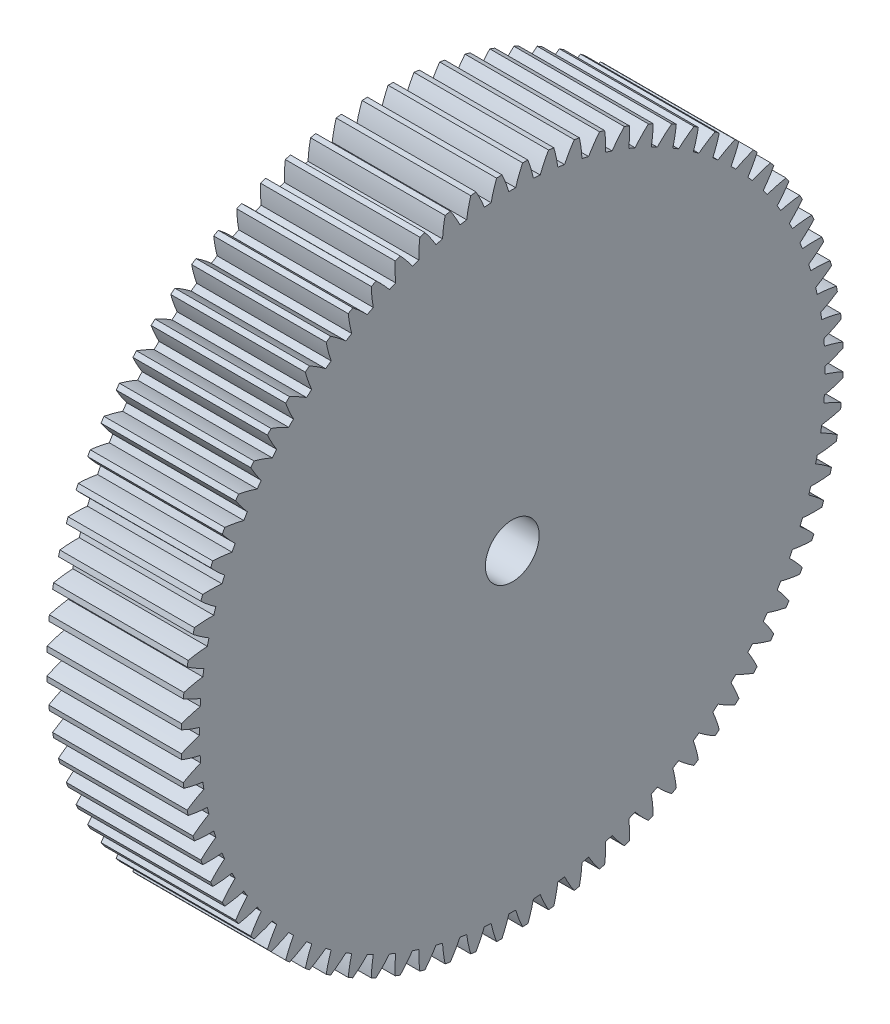
SolidWorks part; units mm, degrees
ref_plane "Plane1" through (0, 0, 0) normal (0, 0, 1) x (1, 0, 0)
ref_plane "Plane2" through (0, 0, 0) normal (0, 1, 0) x (1, 0, 0)
ref_plane "Plane3" through (0, 0, 0) normal (1, 0, 0) x (0, 0, -1)
other "Configuration Table"
sketch "HoldingSke" plane through (0, 0, 0) normal (0, 1, 0) x (1, 0, 0)
  line L0 (0, 0) -> (0.2894, -1.6413)
  line L1 (-15, 0) -> (100, 0) construction
  line L2 (0, 0) -> (-2.1039, 2.3779)
  line L3 (0, 0) -> (-11.863, 4.5341)
  line L4 (0, 0) -> (1.4996, 8.5048)
  line L5 (0, 0) -> (-46.8476, -17.4728)
  line L6 (0, 0) -> (-8.2896, -5.593)
  line L7 (-2.1039, 2.3779) -> (8.6586, 51.2059)
  line L8 (-76.2, 54.61) -> (-75.5, 54.61)
  line L9 (-71.009, 38.7566) -> (-53.1078, 45.2721)
  line L10 (-76.2, 71.12) -> (104.1128, 71.12)
  line L11 (0, 0) -> (-10, 0)
  line L12 (-76.2, 101.6) -> (-76.177, 101.6)
  line L13 (24.9733, 27.94) -> (52.9518, 28.4284)
  line L14 (24.9733, 27.94) -> (24.9743, 27.94)
  line L15 (24.9733, 27.94) -> (100.4006, 29.5858)
  line L16 (-63.627, -0.6) -> (-12.827, -0.6)
  circle A0 centre (0, 0) radius 2
  circle A1 centre (0, 0) radius 23.249
  circle A2 centre (0, 0) radius 37.5
  circle A3 centre (0, 0) radius 2
  dimension "MHD" = 46.498
  dimension "Hub_dia" = 75
  dimension "Bore" = 4
  dimension "MBD" = 4
  dimension "Num_teeth" = 80
  dimension "Pitch" = 1.6667
  dimension "Overall_len" = 50
  dimension "Show_teeth" = 80
  dimension "Thickness" = 10
  dimension "OAL" = 50.0001
  dimension "T_dim" = 0.7
  dimension "Ap" = 20
  dimension "H" = 19.05
  dimension "Pitch_radius" = 180.3128
  dimension "Width" = 10
  dimension "Backlash" = 0.023
  dimension "Addendum_fac" = 1
  dimension "Dedendum_fac" = 1.25
  dimension "Clearance_fac" = 0.25
  dimension "Dedendum_add" = 0.001
  dimension "Module" = 0.6
sketch "BasProSke" plane through (0, 0, 0) normal (0, 1, 0) x (1, 0, 0)
  line L0 (-10, 0) -> (60, 0) construction
  line L1 (0, 0) -> (0, 24.6)
  line L2 (0, 0) -> (10, 0)
  line L3 (10, 0) -> (10, 24.6)
  line L4 (10, 24.6) -> (0, 24.6)
  dimension "Thickness" = 10
  dimension "Diameter" = 49.2
revolve "Base-Revolve" add sketch "BasProSke" angle 360 about L0
sketch "TooCutSke" plane through (0, 0, 0) normal (1, 0, 0) x (0, 0, -1)
  line L1 (0, 0) -> (0, 107) construction
  line L2 (0, 0) -> (-0.5115, 23.9945) construction
  line L3 (0, 0) -> (-1.8842, 47.9553) construction
  line L4 (-0.5115, 23.9945) -> (-0.9421, 23.9776) construction
  arc A0 (0.2526, 23.2476) -> (-0.2526, 23.2476) centre (0, 0) ccw
  arc A1 (0.7803, 24.613) -> (-0.7803, 24.613) centre (0, 0) ccw
  circle A2 centre (0, 0) radius 24 construction
  circle A3 centre (0, 0) radius 22.5526 construction
  arc A4 (-0.2526, 23.2476) -> (-0.7803, 24.613) centre (-9.4448, 20.4796) ccw
  arc A5 (0.7803, 24.613) -> (0.2526, 23.2476) centre (9.4448, 20.4796) ccw
  dimension "Root_dia" = 46.498
  dimension "Overcut_dia" = 49.2508
  dimension "Pitch_dia" = 48
  dimension "Base_dia" = 45.1052
  dimension "Flank_rad" = 9.6
  dimension "Half_ang" = 2.25
  dimension "Half_CT" = 0.431
extrude "ToothCut" cut sketch "TooCutSke" along normal through all
fillet "Breaks" [suppressed] radius 0.012
fillet "RootFillets" [suppressed] radius 0.151
pattern_circular "TeethCuts" count 80 every 4.5 about axis through (-10, 0, 0) along (1, 0, 0) of "ToothCut", "RootFillets", "Breaks"
sketch "HubNeaOneSke" plane through (0, 0, 0) normal (-1, 0, 0) x (0, 0, 1)
  circle A0 centre (0, 0) radius 23.249
  dimension "Diameter" = 46.498
extrude "HubNearOne" [suppressed] add sketch "HubNeaOneSke" along normal blind 40.0001
sketch "HubNeaBotSke" plane through (0, 0, 0) normal (-1, 0, 0) x (0, 0, 1)
  circle A0 centre (0, 0) radius 23.249
  dimension "Diameter" = 46.498
extrude "HubNearBoth" [suppressed] add sketch "HubNeaBotSke" along normal blind 20
ref_plane "FarPln" through (10, 0, 0) normal (1, 0, 0) x (0, 0, -1)
sketch "HubFarSke" plane through (10, 0, 0) normal (1, 0, 0) x (0, 0, -1)
  circle A0 centre (0, 0) radius 23.249
  dimension "Diameter" = 46.498
extrude "HubFar" [suppressed] add sketch "HubFarSke" along normal blind 20
sketch "BorSke" plane through (0, 0, 0) normal (1, 0, 0) x (0, 0, -1)
  circle A0 centre (0, 0) radius 2
  dimension "Diameter" = 4
extrude "Bore" cut sketch "BorSke" along normal mid plane 100.0001
sketch "KeySke" plane through (0, 0, 0) normal (1, 0, 0) x (0, 0, -1)
  line L0 (-0.8, 0) -> (-0.8, 2.7)
  line L1 (-0.8, 2.7) -> (0.8, 2.7)
  line L2 (0.8, 2.7) -> (0.8, 0)
  line L3 (0, 0) -> (0, 34) construction
  line L4 (-0.8, 0) -> (0.8, 0)
  dimension "Offset" = 2.7
  dimension "Width" = 1.6
extrude "Keyway" [suppressed] cut sketch "KeySke" along normal mid plane 100.0001
pattern_circular "Keyway2" [suppressed] count 2 every 90 about axis through (-10, 0, 0) along (1, 0, 0)
equation "' \"Module@HoldingSke\" = 6.35"
equation "' \"Num_teeth@HoldingSke\" = 12"
equation "' \"Ap@HoldingSke\" =  20"
equation "' \"Ap@HoldingSke\" = 20"
equation "' \"Width@HoldingSke\" = 0.5 * 25.4"
equation "' \"Hub_dia@HoldingSke\"= 1 * 25.4"
equation "' \"Hub_dia@HoldingSke\" = 1 * 25.4"
equation "' \"Overall_len@HoldingSke\" = 1.0 * 25.4"
equation "' \"Bore@HoldingSke\" = 0.75 * 25.4"
equation "' \"T_dim@HoldingSke\" = 0.1 * 25.4"
equation "' \"Width@KeySke\" = 0.25 * 25.4"
equation "' \"Show_teeth@HoldingSke\" = 13"
equation "' \"Backlash@HoldingSke\" = 0.009 * 25.4"
equation "' \"Addendum_fac@HoldingSke\" = 1.0"
equation "' \"Dedendum_fac@HoldingSke\" = 1.25"
equation "' \"Dedendum_add@HoldingSke\" = 0.00005 * 25.4"
equation "' \"Clearance_fac@HoldingSke\" = 0.25"
equation "\"Pitch@HoldingSke\" = 1 / \"Module@HoldingSke\""
equation "\"Overcut_dia@TooCutSke\" = (\"Num_teeth@HoldingSke\" + 2 * \"Addendum_fac@HoldingSke\") / \"Pitch@HoldingSke\" + 0.002 * 25.4"
equation "\"Pitch_dia@TooCutSke\" = \"Num_teeth@HoldingSke\" / \"Pitch@HoldingSke\""
equation "\"Base_dia@TooCutSke\" = \"Num_teeth@HoldingSke\" / \"Pitch@HoldingSke\" * cos((\"Ap@HoldingSke\"  * 3.14159265 / 180))"
equation "\"Root_dia@TooCutSke\" = (\"Num_teeth@HoldingSke\" + 2) / \"Pitch@HoldingSke\" - 2 * (\"Addendum_fac@HoldingSke\" + \"Dedendum_fac@HoldingSke\") / \"Pitch@HoldingSke\" - \"Dedendum_add@HoldingSke\" * 2"
equation "\"Half_ang@TooCutSke\" = 180 / \"Num_teeth@HoldingSke\""
equation "\"Half_CT@TooCutSke\" = \"Num_teeth@HoldingSke\" / \"Pitch@HoldingSke\" * sin((3.14159265 / 2 / \"Num_teeth@HoldingSke\")) / 2 - 7 * \"Backlash@HoldingSke\" / 4"
equation "\"Flank_rad@TooCutSke\" = \"Num_teeth@HoldingSke\" / \"Pitch@HoldingSke\" / 5"
equation "\"Radius@RootFillets\" = \"Clearance_fac@HoldingSke\" / \"Pitch@HoldingSke\" + \"Dedendum_add@HoldingSke\""
equation "\"Break_rad@Breaks\" = 0.02 / \"Pitch@HoldingSke\""
equation "\"Thickness@HoldingSke\" = \"Width@HoldingSke\""
equation "\"OAL@HoldingSke\" = \"Thickness@HoldingSke\""
equation "\"MHD@HoldingSke\" = (\"Num_teeth@HoldingSke\" + 2) / \"Pitch@HoldingSke\" - 2 * (\"Addendum_fac@HoldingSke\" + \"Dedendum_fac@HoldingSke\")  / \"Pitch@HoldingSke\" - \"Dedendum_add@HoldingSke\" * 2"
equation "\"MBD@HoldingSke\" = (\"Num_teeth@HoldingSke\" + 2) / \"Pitch@HoldingSke\" - 2 * (\"Addendum_fac@HoldingSke\" + \"Dedendum_fac@HoldingSke\")  / \"Pitch@HoldingSke\" - \"Dedendum_add@HoldingSke\" * 2 - 0.002 * 25.4"
equation "\"MHD@HoldingSke\" = ((sgn( \"MHD@HoldingSke\" - \"Hub_dia@HoldingSke\" )-1)*( \"MHD@HoldingSke\" - \"Hub_dia@HoldingSke\" ))/-2+ \"Hub_dia@HoldingSke\""
equation "\"MBD@HoldingSke\" = ((sgn( \"MBD@HoldingSke\" - \"Bore@HoldingSke\" )-1)*( \"MBD@HoldingSke\" - \"Bore@HoldingSke\" ))/-2+ \"Bore@HoldingSke\""
equation "\"OAL@HoldingSke\" = ((sgn( \"OAL@HoldingSke\" - \"Overall_len@HoldingSke\" )+1)*( \"OAL@HoldingSke\" - \"Overall_len@HoldingSke\" ))/2 + \"Overall_len@HoldingSke\" + 0.000002 * 25.4"
equation "\"Num_teeth@TeethCuts\" = int( \"Show_teeth@HoldingSke\" ) + 1"
equation "\"Num_teeth@TeethCuts\" = ((sgn( \"Num_teeth@TeethCuts\" - \"Num_teeth@HoldingSke\" )-1)*( \"Num_teeth@TeethCuts\" - \"Num_teeth@HoldingSke\" ))/-2+ \"Num_teeth@HoldingSke\""
equation "\"Num_teeth@TeethCuts\" = ((sgn( \"Num_teeth@TeethCuts\" - 2.0)+1)*( \"Num_teeth@TeethCuts\" - 2.0))/2 +2.0"
equation "\"Angle@TeethCuts\" = 360.0 / \"Num_teeth@HoldingSke\""
equation "\"Diameter@BasProSke\" = (\"Num_teeth@HoldingSke\" + 2 * \"Addendum_fac@HoldingSke\") / \"Pitch@HoldingSke\""
equation "\"Thickness@BasProSke\"  = \"Thickness@HoldingSke\""
equation "' \"Fillet_rad@BasProSke\" =  \"Thickness@HoldingSke\" * 0.05"
equation "' \"Fillet_rad@BasProSke\" = \"Thickness@HoldingSke\" * 0.05"
equation "\"MHD@HoldingSke\" = ((sgn( \"MHD@HoldingSke\" - \"Root_dia@TooCutSke\" )-1)*( \"MHD@HoldingSke\" - \"Root_dia@TooCutSke\" ))/-2+ \"Root_dia@TooCutSke\""
equation "\"Diameter@HubNeaOneSke\" = \"MHD@HoldingSke\""
equation "\"Length@HubNearOne\" = \"OAL@HoldingSke\" - \"Thickness@BasProSke\""
equation "\"Diameter@HubNeaBotSke\" = \"MHD@HoldingSke\""
equation "\"Length@HubNearBoth\" = ( \"OAL@HoldingSke\" - \"Thickness@BasProSke\" ) / 2.0"
equation "\"Thickness@FarPln\" = \"Thickness@BasProSke\""
equation "\"Diameter@HubFarSke\" = \"MHD@HoldingSke\""
equation "\"Length@HubFar\" = ( \"OAL@HoldingSke\" - \"Thickness@BasProSke\" ) / 2.0"
equation "\"Diameter@BorSke\" = \"MBD@HoldingSke\""
equation "\"D1@Bore\" = \"OAL@HoldingSke\" * 2.0"
equation "\"D1@Keyway\" = \"OAL@HoldingSke\" * 2.0"
equation "\"Offset@KeySke\" = \"T_dim@HoldingSke\" + \"MBD@HoldingSke\" / 2.0"
